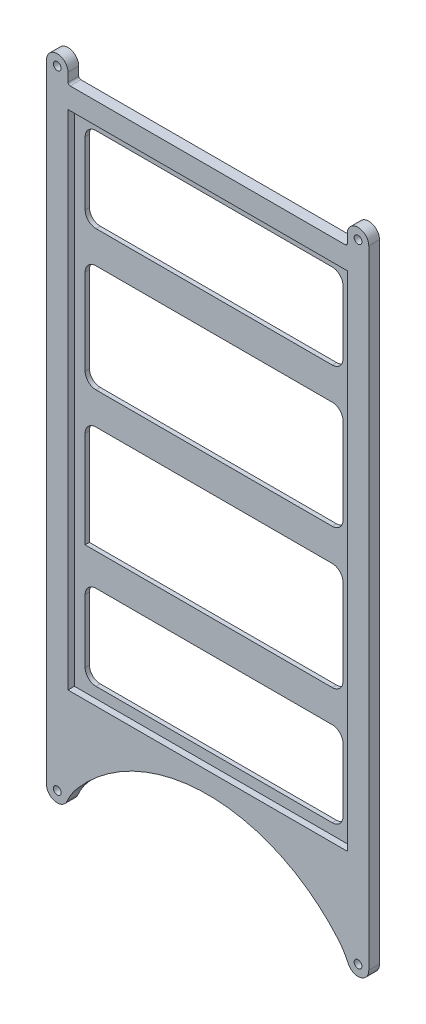
SolidWorks part; units mm, degrees
ref_plane "Front" through (0, 0, 0) normal (0, 0, 1) x (1, 0, 0)
ref_plane "Top" through (0, 0, 0) normal (0, 1, 0) x (1, 0, 0)
ref_plane "Right" through (0, 0, 0) normal (1, 0, 0) x (0, 0, -1)
sketch "Эскиз2" plane through (0, 0, 0) normal (0, 0, 1) x (1, 0, 0)
  line L0 (-69.5, 0) -> (-64, 0) construction
  line L1 (-65, 5) -> (-65, 1)
  line L2 (65, 5) -> (65, 1)
  line L3 (64, 0) -> (-64, 0)
  line L4 (-75, 5) -> (-75, -287)
  line L5 (75, 5) -> (75, -287)
  arc A0 (-75, 5) -> (-65, 5) centre (-70, 5) cw
  arc A1 (-65, 5) -> (-75, 5) centre (-70, 5) ccw construction
  arc A2 (65, 5) -> (75, 5) centre (70, 5) cw
  arc A3 (-75, -287) -> (-65.4238, -289.0145) centre (-70, -287) ccw
  arc A4 (65.4238, -289.0145) -> (75, -287) centre (70, -287) ccw
  arc A5 (65, -287) -> (75, -287) centre (70, -287) ccw construction
  circle A6 centre (70, -287) radius 1.8
  circle A7 centre (-70, -287) radius 1.8
  circle A8 centre (-70, 5) radius 1.8
  circle A9 centre (70, 5) radius 1.8
  arc A10 (64, 0) -> (65, 1) centre (64, 1) ccw
  arc A11 (-65, 1) -> (-64, 0) centre (-64, 1) ccw
  arc A12 (-65, 1) -> (-64, 0) centre (-64, 1) ccw construction
  arc A13 (-60.7464, -281.5805) -> (60.7464, -281.5805) centre (0, -333.6369) cw
  arc A14 (65.4238, -289.0145) -> (60.7464, -281.5805) centre (37.9665, -301.1016) ccw
  arc A15 (-65.4238, -289.0145) -> (-60.7464, -281.5805) centre (-37.9665, -301.1016) cw
  point P47 (65, -287)
  point P50 (-65, -287)
  dimension "D1" = 30
  dimension "D3" = 1
  dimension "D4" = 3.6
  dimension "D5" = 3.6
  dimension "D6" = 5
  dimension "D7" = 3.6
  dimension "D2" = 333.6369
extrude "Бобышка-Вытянуть1" add sketch "Эскиз2" along normal blind 5
sketch "Эскиз3" plane through (0, 0, 5) normal (0, 0, 1) x (1, 0, 0)
  line L0 (-75, 5) -> (-75, -287) construction
  line L1 (-65, -10) -> (65, -10)
  line L2 (-65, -10) -> (-65, -244)
  line L3 (-65, -244) -> (65, -244)
  line L4 (65, -10) -> (65, -244)
  line L5 (75, -287) -> (75, 5) construction
  line L6 (64, 0) -> (-64, 0) construction
  dimension "D1" = 10
  dimension "D2" = 10
  dimension "D3" = 10
  dimension "D4" = 234
extrude "Вырез-Вытянуть1" cut sketch "Эскиз3" against normal blind 3
sketch "Эскиз4" plane through (0, 0, 2) normal (0, 0, 1) x (1, 0, 0)
  line L0 (65, -10) -> (-65, -10) construction
  line L1 (-55, -15) -> (55, -15)
  line L2 (-60, -20) -> (-60, -49.5)
  line L3 (-55, -239) -> (55, -239)
  line L4 (60, -20) -> (60, -49.5)
  line L5 (-65, -244) -> (65, -244) construction
  line L6 (65, -244) -> (65, -10) construction
  line L7 (-65, -10) -> (-65, -244) construction
  line L8 (-60, -15) -> (60, -239) construction
  line L9 (60, -15) -> (-60, -239) construction
  line L10 (-60, -204.5) -> (-60, -234)
  line L11 (55, -119.5) -> (-55, -119.5)
  line L12 (-60, -139.5) -> (-60, -184.5)
  line L13 (55, -134.5) -> (-55, -134.5)
  line L14 (-60, -74.5) -> (-60, -114.5)
  line L15 (60, -119.5) -> (-60, -134.5) construction
  line L16 (60, -134.5) -> (-60, -119.5) construction
  line L17 (-60, -184.5) -> (55, -184.5)
  line L18 (60, -204.5) -> (60, -234)
  line L19 (-55, -199.5) -> (55, -199.5)
  line L20 (60, -139.5) -> (60, -179.5)
  line L21 (-55, -69.5) -> (55, -69.5)
  line L22 (60, -74.5) -> (60, -114.5)
  line L23 (-55, -54.5) -> (55, -54.5)
  arc A0 (60, -234) -> (55, -239) centre (55, -234) cw
  arc A1 (-55, -239) -> (-60, -234) centre (-55, -234) cw
  arc A2 (-55, -199.5) -> (-60, -204.5) centre (-55, -204.5) ccw
  arc A3 (60, -204.5) -> (55, -199.5) centre (55, -204.5) ccw
  arc A4 (60, -179.5) -> (55, -184.5) centre (55, -179.5) cw
  arc A5 (55, -134.5) -> (60, -139.5) centre (55, -139.5) cw
  arc A6 (-55, -134.5) -> (-60, -139.5) centre (-55, -139.5) ccw
  arc A7 (-60, -114.5) -> (-55, -119.5) centre (-55, -114.5) ccw
  arc A8 (60, -114.5) -> (55, -119.5) centre (55, -114.5) cw
  arc A9 (60, -74.5) -> (55, -69.5) centre (55, -74.5) ccw
  arc A10 (-60, -74.5) -> (-55, -69.5) centre (-55, -74.5) cw
  arc A11 (-60, -49.5) -> (-55, -54.5) centre (-55, -49.5) ccw
  arc A12 (55, -54.5) -> (60, -49.5) centre (55, -49.5) ccw
  arc A13 (60, -20) -> (55, -15) centre (55, -20) ccw
  arc A14 (-55, -15) -> (-60, -20) centre (-55, -20) ccw
  point P12 (0, -127)
  point P35 (60, -199.5)
  point P54 (-60, -69.5)
  dimension "D9" = 5
  dimension "D1" = 5
  dimension "D2" = 5
  dimension "D3" = 5
  dimension "D4" = 5
  dimension "D5" = 50
  dimension "D6" = 50
  dimension "D7" = 15
  dimension "D8" = 15
extrude "Вырез-Вытянуть2" cut sketch "Эскиз4" against normal through all
